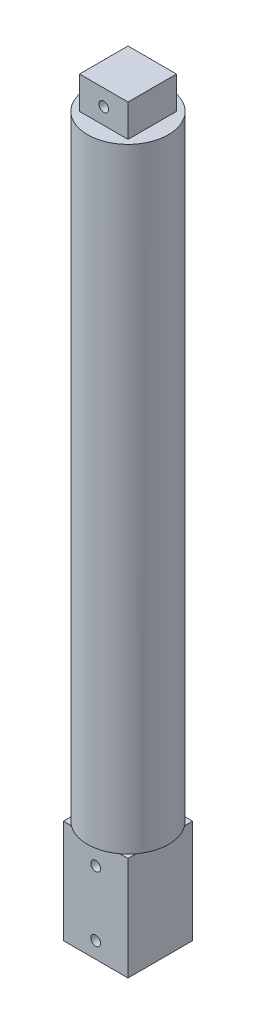
SolidWorks part; units mm, degrees
ref_plane "Front Plane" through (0, 0, 0) normal (0, 0, 1) x (1, 0, 0)
ref_plane "Top Plane" through (0, 0, 0) normal (0, 1, 0) x (1, 0, 0)
ref_plane "Right Plane" through (0, 0, 0) normal (1, 0, 0) x (0, 0, -1)
sketch "Sketch1" plane through (0, 0, 0) normal (0, 0, 1) x (1, 0, 0)
  line L0 (0, 0) -> (0, -14105.0389) construction
  line L1 (-10, 32) -> (10, 32)
  line L2 (-10, 32) -> (-10, 0)
  line L3 (-10, 0) -> (10, 0)
  line L4 (10, 32) -> (10, 0)
  circle A0 centre (0, 5) radius 1.5
  circle A1 centre (0, 25) radius 1.5
  point P5 (0, 0)
  dimension "D4" = 3
  dimension "D5" = 3
  dimension "D1" = 20
  dimension "D2" = 32
  dimension "D3" = 20
  dimension "D6" = 5
extrude "Boss-Extrude1" add sketch "Sketch1" along normal mid plane 20
sketch "Sketch3" plane through (0, 32, 0) normal (0, 1, 0) x (1, 0, 0)
  circle A0 centre (0, 0) radius 12.5
  dimension "D1" = 25
extrude "Boss-Extrude2" add sketch "Sketch3" along normal blind 200
sketch "Sketch4" plane through (0, 232, 0) normal (0, 1, 0) x (1, 0, 0)
  line L1 (-7.5, 7.5) -> (7.5, 7.5)
  line L2 (-7.5, 7.5) -> (-7.5, -7.5)
  line L3 (-7.5, -7.5) -> (7.5, -7.5)
  line L4 (7.5, 7.5) -> (7.5, -7.5)
  line L5 (-7.5, 7.5) -> (7.5, -7.5) construction
  line L6 (-7.5, -7.5) -> (7.5, 7.5) construction
  point P0 (0, 0)
  dimension "D1" = 15
  dimension "D2" = 15
extrude "Cut-Extrude1" cut sketch "Sketch4" against normal blind 10 flip side to cut
sketch "Sketch5" plane through (0, 0, 7.5) normal (0, 0, 1) x (1, 0, 0)
  line L0 (-7.5, 227) -> (7.5, 227) construction
  line L1 (-7.5, 222) -> (-7.5, 232) construction
  line L2 (7.5, 222) -> (7.5, 232) construction
  line L3 (0, 232) -> (0, 222) construction
  line L4 (-7.5, 232) -> (7.5, 232) construction
  line L5 (12.5, 222) -> (-12.5, 222) construction
  circle A0 centre (0, 227) radius 1.5
  dimension "D1" = 3
extrude "Cut-Extrude2" cut sketch "Sketch5" against normal through all
